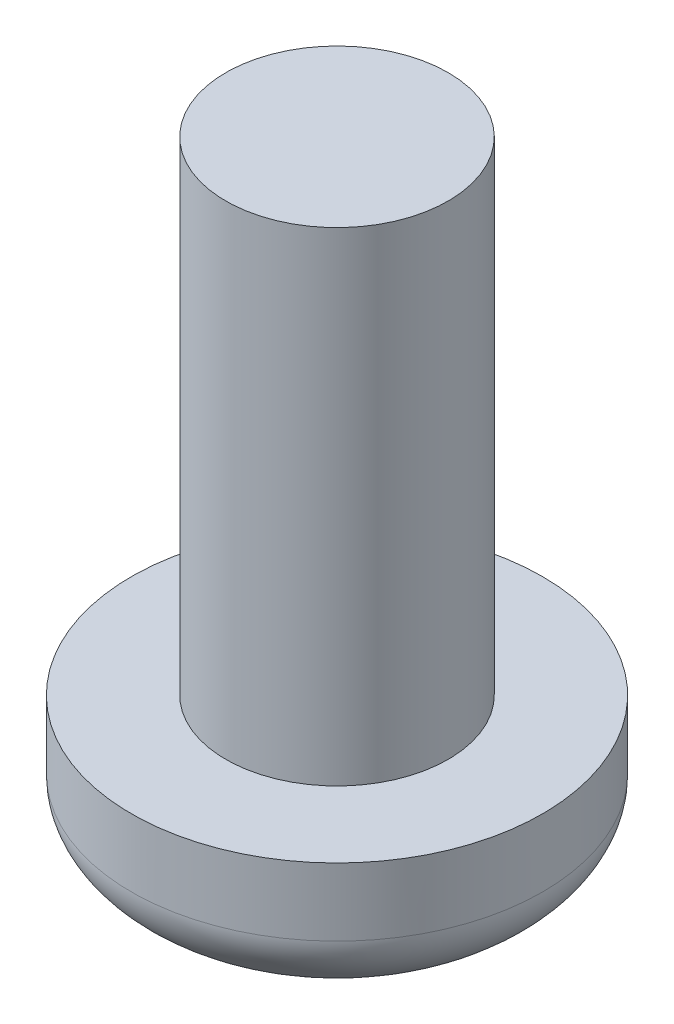
SolidWorks part; units mm, degrees
ref_plane "Front Plane" through (0, 0, 0) normal (0, 0, 1) x (1, 0, 0)
ref_plane "Top Plane" through (0, 0, 0) normal (0, 1, 0) x (1, 0, 0)
ref_plane "Right Plane" through (0, 0, 0) normal (1, 0, 0) x (0, 0, -1)
other "Default"
sketch "Sketch1" plane through (0, 0, 0) normal (0, 0, 1) x (1, 0, 0)
  line L0 (0, -1.1348) -> (0, 2.3632) construction
  line L1 (0, -3.5) -> (0, 10)
  line L2 (0, 10) -> (2.3, 10)
  line L3 (2.3, 10) -> (2.3, 0)
  line L4 (2.3, 0) -> (4.25, 0)
  line L5 (4.25, 0) -> (4.25, -1.4)
  ellipse E0 centre (0, -1.4) end of major axis (4.25, -1.4) minor radius 2.1 (4.25, -1.4) -> (0, -3.5) cw
  point P1 (1.1795, -0.0982)
  point P9 (0, 0)
  point P10 (0, 0)
  point P11 (0, 0)
  point P16 (0, 0)
  point P19 (4.2121, -0.8347)
  point P20 (0, 0)
  dimension "Length" = 10
  dimension "D2" = 4.6
  dimension "D3" = 8.5
  dimension "D4" = 3.5
  dimension "D5" = 1.4
revolve "Revolve1" add sketch "Sketch1" angle 360 about L0
